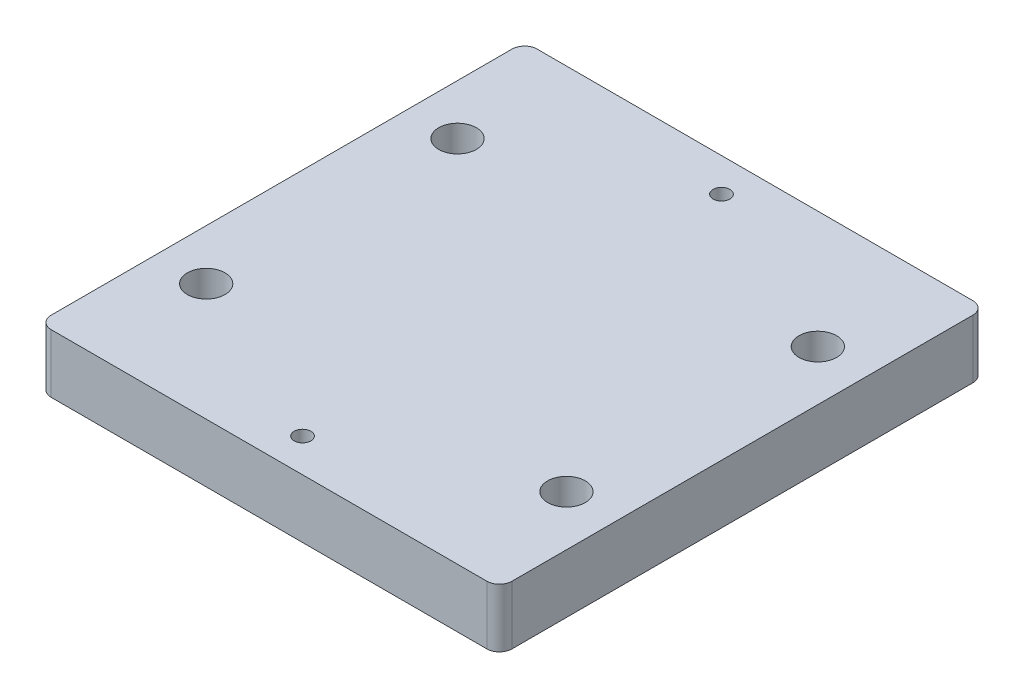
SolidWorks part; units mm, degrees
ref_plane "前视基准面" through (0, 0, 0) normal (0, 0, 1) x (1, 0, 0)
ref_plane "上视基准面" through (0, 0, 0) normal (0, 1, 0) x (1, 0, 0)
ref_plane "右视基准面" through (0, 0, 0) normal (1, 0, 0) x (0, 0, -1)
sketch "草图1" plane through (0, 0, 0) normal (0, 1, 0) x (1, 0, 0)
  line L0 (0, 58) -> (0, -58) construction
  line L1 (-55, 58) -> (55, 58)
  line L2 (-55, 58) -> (-55, -58)
  line L3 (-55, -58) -> (55, -58)
  line L4 (55, 58) -> (55, -58)
  line L5 (-55, 0) -> (55, 0) construction
  circle A0 centre (-43, 30) radius 4.5
  circle A1 centre (43, 30) radius 4.5
  circle A2 centre (43, -30) radius 4.5
  circle A3 centre (-43, -30) radius 4.5
  circle A4 centre (0, -50) radius 2
  circle A5 centre (0, 50) radius 2
  dimension "D5" = 9
  dimension "D10" = 4
  dimension "D1" = 116
  dimension "D2" = 110
  dimension "D3" = 55
  dimension "D4" = 58
  dimension "D6" = 30
  dimension "D7" = 12
  dimension "D11" = 8
  dimension "D8" = 2
  dimension "D9" = 2
extrude "凸台-拉伸1" add sketch "草图1" along normal blind 14
fillet "圆角1" radius 3 4 edges at (-55, 7, -58) (55, 7, -58) (55, 7, 58) (-55, 7, 58)
